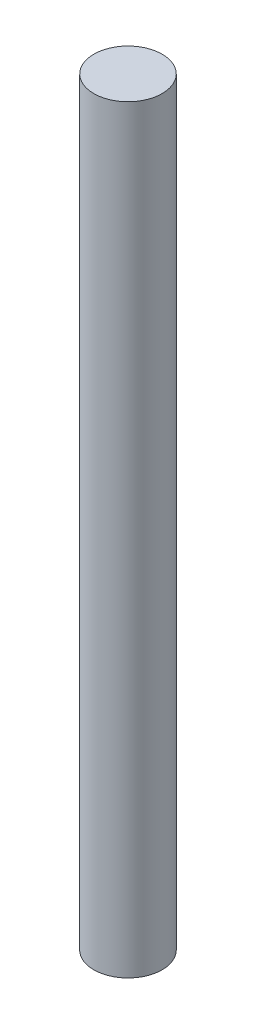
SolidWorks part; units mm, degrees
ref_plane "Front Plane" through (0, 0, 0) normal (0, 0, 1) x (1, 0, 0)
ref_plane "Top Plane" through (0, 0, 0) normal (0, 1, 0) x (1, 0, 0)
ref_plane "Right Plane" through (0, 0, 0) normal (1, 0, 0) x (0, 0, -1)
sketch "Sketch1" plane through (0, 0, 0) normal (0, 1, 0) x (1, 0, 0)
  circle A0 centre (0, 0) radius 4.5
  dimension "D1" = 9
extrude "Boss-Extrude1" add sketch "Sketch1" along normal blind 100
sketch "Sketch2" plane through (0, 0, 0) normal (0, -1, 0) x (1, 0, 0)
  circle A0 centre (0, 0) radius 10
  circle A1 centre (0, 22) radius 5
  circle A2 centre (0, -22) radius 5
  dimension "D2" = 10
  dimension "D3" = 20
  dimension "D4" = 10
  dimension "D1" = 22
  dimension "D5" = 22
